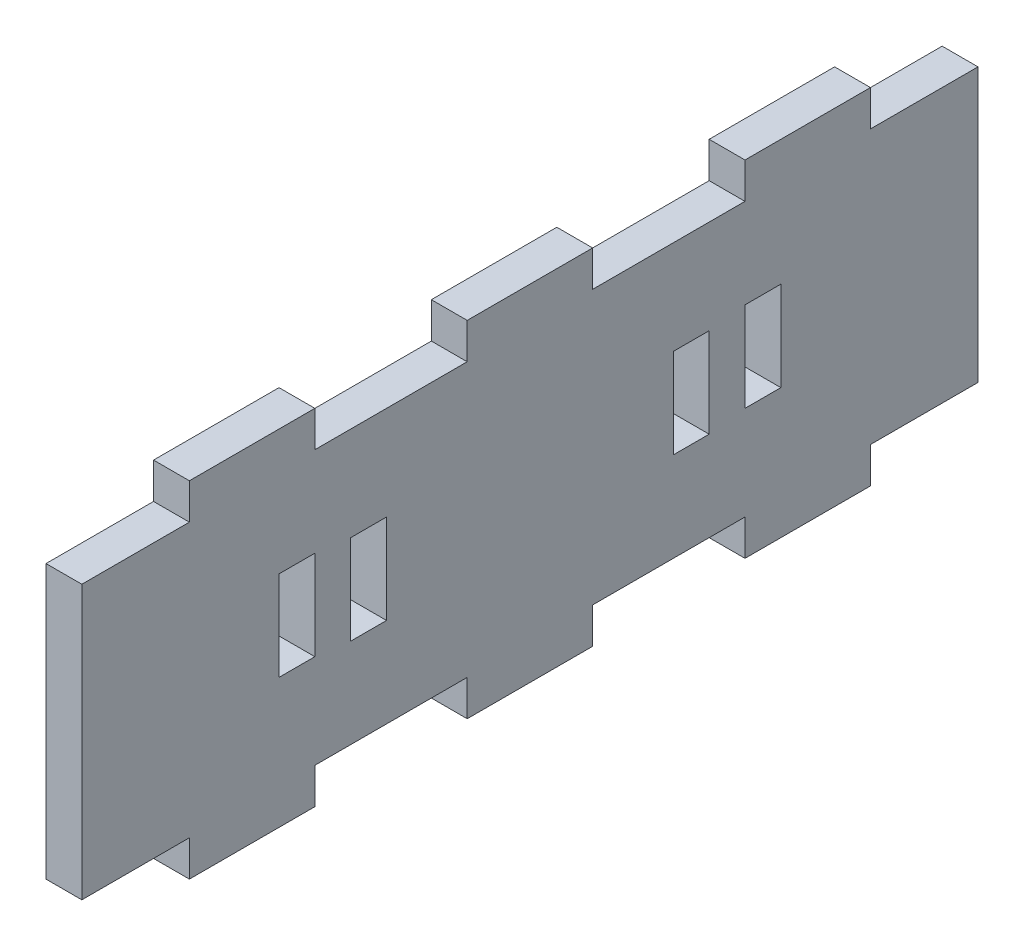
SolidWorks part; units mm, degrees
ref_plane "Front Plane" through (0, 0, 0) normal (0, 0, 1) x (1, 0, 0)
ref_plane "Top Plane" through (0, 0, 0) normal (0, 1, 0) x (1, 0, 0)
ref_plane "Right Plane" through (0, 0, 0) normal (1, 0, 0) x (0, 0, -1)
sketch "Sketch1" plane through (0, 0, 0) normal (1, 0, 0) x (0, 0, -1)
  line L1 (-25, 7.625) -> (25, 7.625)
  line L2 (-25, 7.625) -> (-25, -7.625)
  line L3 (-25, -7.625) -> (25, -7.625)
  line L4 (25, 7.625) -> (25, -7.625)
  line L5 (-25, 7.625) -> (25, -7.625) construction
  line L6 (-25, -7.625) -> (25, 7.625) construction
  line L7 (-19, -7.625) -> (-12, -7.625)
  line L8 (-19, -7.625) -> (-19, -9.625)
  line L9 (-19, -9.625) -> (-12, -9.625)
  line L10 (-12, -7.625) -> (-12, -9.625)
  line L11 (-3.5, -7.625) -> (3.5, -7.625)
  line L12 (-3.5, -7.625) -> (-3.5, -9.625)
  line L13 (-3.5, -9.625) -> (3.5, -9.625)
  line L14 (3.5, -7.625) -> (3.5, -9.625)
  line L15 (12, -7.625) -> (19, -7.625)
  line L16 (12, -7.625) -> (12, -9.625)
  line L17 (12, -9.625) -> (19, -9.625)
  line L18 (19, -7.625) -> (19, -9.625)
  line L19 (-19, 7.625) -> (-12, 7.625)
  line L20 (-19, 7.625) -> (-19, 9.625)
  line L21 (-19, 9.625) -> (-12, 9.625)
  line L22 (-12, 7.625) -> (-12, 9.625)
  line L23 (-3.5, 7.625) -> (3.5, 7.625)
  line L24 (-3.5, 7.625) -> (-3.5, 9.625)
  line L25 (-3.5, 9.625) -> (3.5, 9.625)
  line L26 (3.5, 7.625) -> (3.5, 9.625)
  line L27 (12, 7.625) -> (19, 7.625)
  line L28 (12, 7.625) -> (12, 9.625)
  line L29 (12, 9.625) -> (19, 9.625)
  line L30 (19, 7.625) -> (19, 9.625)
  line L31 (-10, 2.375) -> (-8, 2.375)
  line L32 (-10, 2.375) -> (-10, -2.625)
  line L33 (-10, -2.625) -> (-8, -2.625)
  line L34 (-8, 2.375) -> (-8, -2.625)
  line L35 (8, 2.375) -> (10, 2.375)
  line L36 (8, 2.375) -> (8, -2.625)
  line L37 (8, -2.625) -> (10, -2.625)
  line L38 (10, 2.375) -> (10, -2.625)
  line L39 (-14, 2.625) -> (-12, 2.625)
  line L40 (-14, 2.625) -> (-14, -2.375)
  line L41 (-14, -2.375) -> (-12, -2.375)
  line L42 (-12, 2.625) -> (-12, -2.375)
  line L43 (12, 2.625) -> (14, 2.625)
  line L44 (12, 2.625) -> (12, -2.375)
  line L45 (12, -2.375) -> (14, -2.375)
  line L46 (14, 2.625) -> (14, -2.375)
  point P0 (0, 0)
  dimension "D1" = 50
  dimension "D2" = 7
  dimension "D3" = 7
  dimension "D4" = 7
  dimension "D5" = 7
  dimension "D6" = 7
  dimension "D7" = 7
  dimension "D8" = 6
  dimension "D9" = 8.5
  dimension "D10" = 8.5
  dimension "D11" = 6
  dimension "D12" = 6
  dimension "D13" = 8.5
  dimension "D14" = 8.5
  dimension "D15" = 6
  dimension "D16" = 15.25
  dimension "D17" = 2
  dimension "D18" = 2
  dimension "D19" = 2
  dimension "D20" = 2
  dimension "D21" = 2
  dimension "D22" = 2
  dimension "D23" = 5
  dimension "D24" = 5
  dimension "D25" = 5
  dimension "D26" = 5
  dimension "D27" = 5
  dimension "D28" = 5
  dimension "D29" = 5
  dimension "D30" = 5
  dimension "D31" = 15
  dimension "D32" = 15
  dimension "D33" = 16
  dimension "D34" = 24
  dimension "D35" = 6
  dimension "D36" = 6
  dimension "D37" = 11
  dimension "D38" = 11
extrude "Boss-Extrude1" add sketch "Sketch1" along normal blind 2 contours L4 L1 L2 L3 | L1 L26 L25 L24 | L1 L30 L29 L28 | L18 L3 L16 L17 | L14 L3 L12 L13 | L10 L3 L8 L9 | L22 L21 L20 L19
